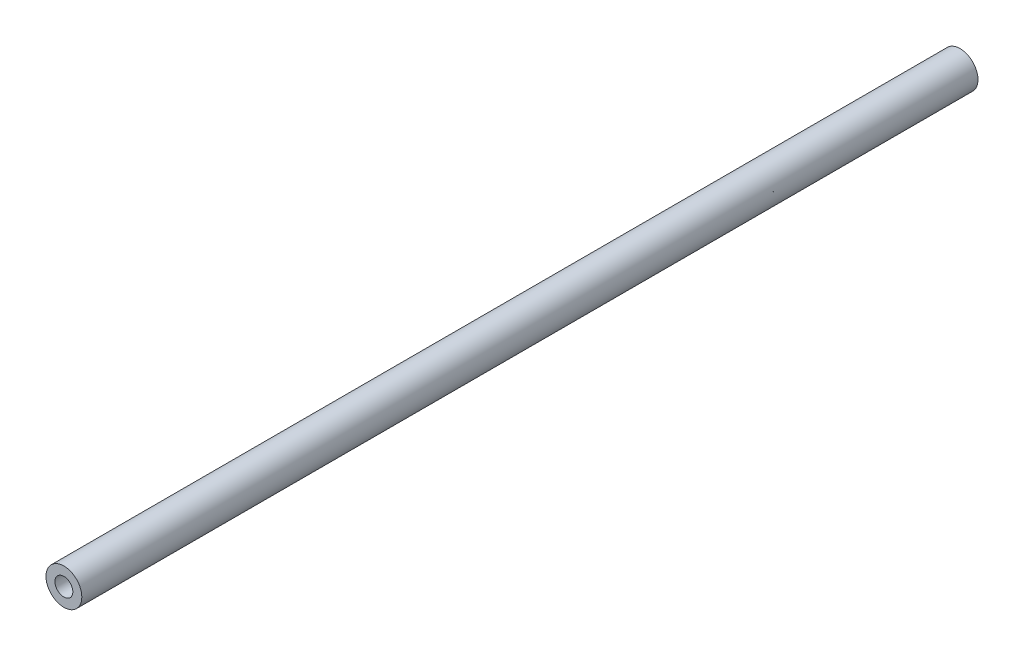
SolidWorks part; units mm, degrees
ref_plane "前视基准面" through (0, 0, 0) normal (0, 0, 1) x (1, 0, 0)
ref_plane "上视基准面" through (0, 0, 0) normal (0, 1, 0) x (1, 0, 0)
ref_plane "右视基准面" through (0, 0, 0) normal (1, 0, 0) x (0, 0, -1)
sketch "草图1" plane through (0, 0, 0) normal (0, 0, 1) x (1, 0, 0)
  circle A0 centre (0, 0) radius 4
  dimension "D1" = 8
extrude "凸台-拉伸1" add sketch "草图1" along normal blind 200
sketch "草图2" plane through (0, 0, 0) normal (0, 0, -1) x (-1, 0, 0)
  circle A0 centre (0, 0) radius 2
  dimension "D1" = 4
extrude "切除-拉伸1" cut sketch "草图2" against normal through all both and the other way through all
